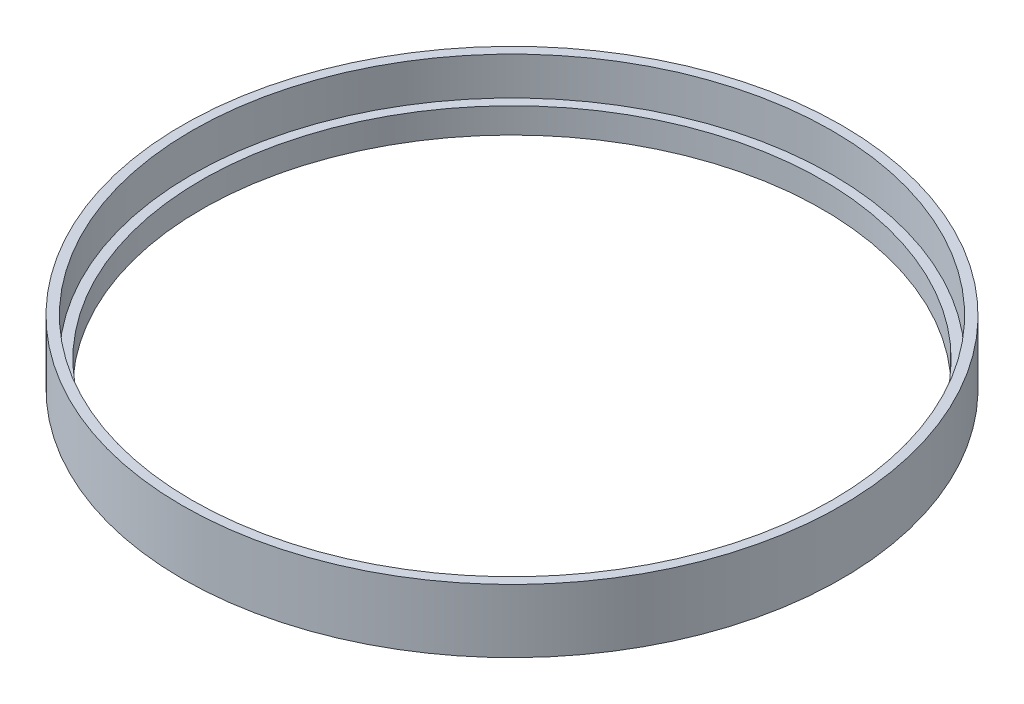
SolidWorks part; units mm, degrees
ref_plane "Alzado" through (0, 0, 0) normal (0, 0, 1) x (1, 0, 0)
ref_plane "Planta" through (0, 0, 0) normal (0, 1, 0) x (1, 0, 0)
ref_plane "Vista lateral" through (0, 0, 0) normal (1, 0, 0) x (0, 0, -1)
sketch "Croquis1" plane through (0, 0, 0) normal (0, 1, 0) x (1, 0, 0)
  circle A0 centre (0, 0) radius 26
  dimension "D1" = 52
extrude "Saliente-Extruir1" add sketch "Croquis1" along normal blind 5
sketch "Croquis2" plane through (0, 5, 0) normal (0, 1, 0) x (1, 0, 0)
  circle A0 centre (0, 0) radius 25.25
  dimension "D1" = 50.5
extrude "Cortar-Extruir1" cut sketch "Croquis2" against normal blind 3
sketch "Croquis3" plane through (0, 2, 0) normal (0, 1, 0) x (1, 0, 0)
  circle A0 centre (0, 0) radius 24.5
  dimension "D1" = 49
extrude "Cortar-Extruir2" cut sketch "Croquis3" against normal blind 3
